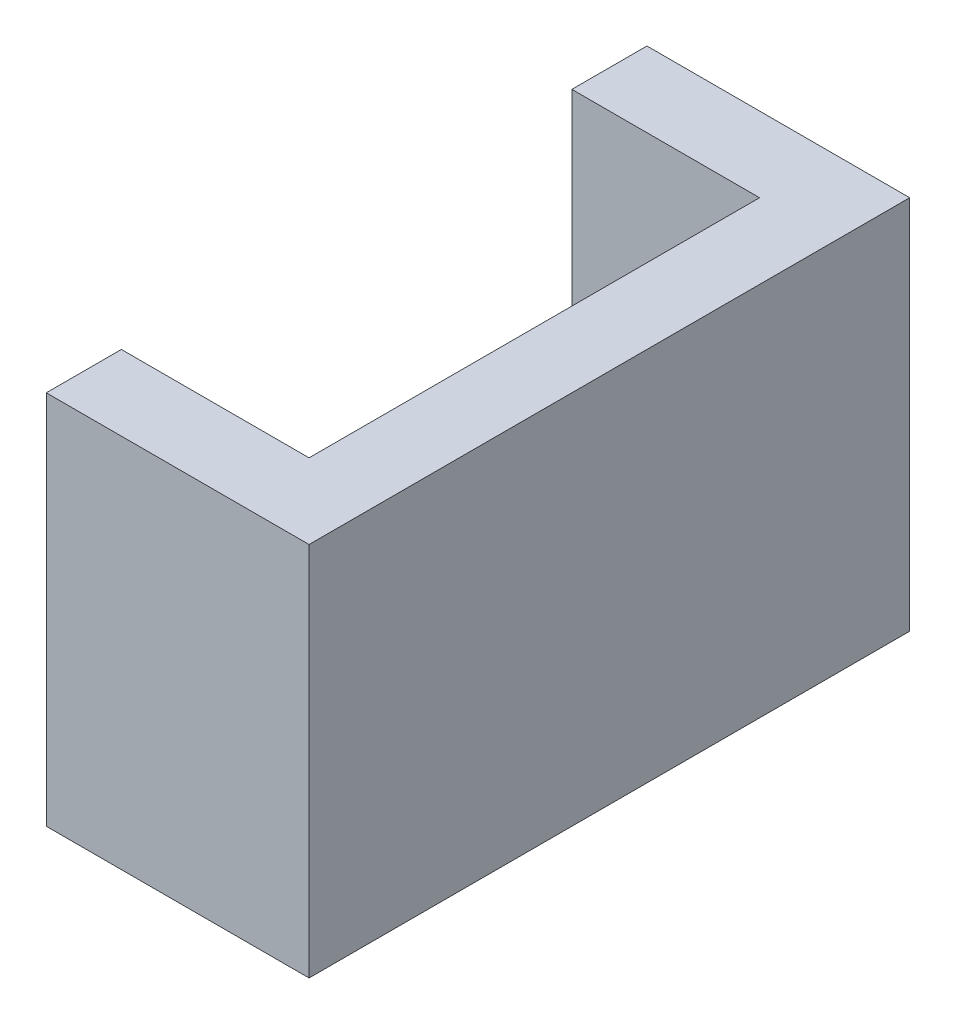
SolidWorks part; units mm, degrees
ref_plane "Front Plane" through (0, 0, 0) normal (0, 0, 1) x (1, 0, 0)
ref_plane "Top Plane" through (0, 0, 0) normal (0, 1, 0) x (1, 0, 0)
ref_plane "Right Plane" through (0, 0, 0) normal (1, 0, 0) x (0, 0, -1)
sketch "Sketch1" plane through (0, 0, 0) normal (1, 0, 0) x (0, 0, -1)
  line L1 (-7.1518, 4.1446) -> (8.8482, 4.1446)
  line L2 (-7.1518, 4.1446) -> (-7.1518, -5.8554)
  line L3 (-7.1518, -5.8554) -> (8.8482, -5.8554)
  line L4 (8.8482, 4.1446) -> (8.8482, -5.8554)
  dimension "D1" = 16
  dimension "D2" = 10
extrude "Boss-Extrude1" add sketch "Sketch1" along normal blind 7
sketch "Sketch2" plane through (0, -5.8554, 0) normal (0, -1, 0) x (-1, 0, 0)
  line L0 (0, -7.1518) -> (0, 8.8482) construction
  line L1 (0, -5.1518) -> (-5, -5.1518)
  line L2 (0, -5.1518) -> (0, 6.8482)
  line L3 (0, 6.8482) -> (-5, 6.8482)
  line L4 (-5, -5.1518) -> (-5, 6.8482)
  line L5 (-7, -7.1518) -> (0, -7.1518) construction
  line L6 (-7, -7.1518) -> (-7, 8.8482) construction
  line L7 (-7, 8.8482) -> (0, 8.8482) construction
  dimension "D1" = 2
  dimension "D2" = 2
  dimension "D3" = 2
extrude "Cut-Extrude1" cut sketch "Sketch2" against normal up to surface (10 mm away) up to face at (3.5, 4.1446, -0.8482)
